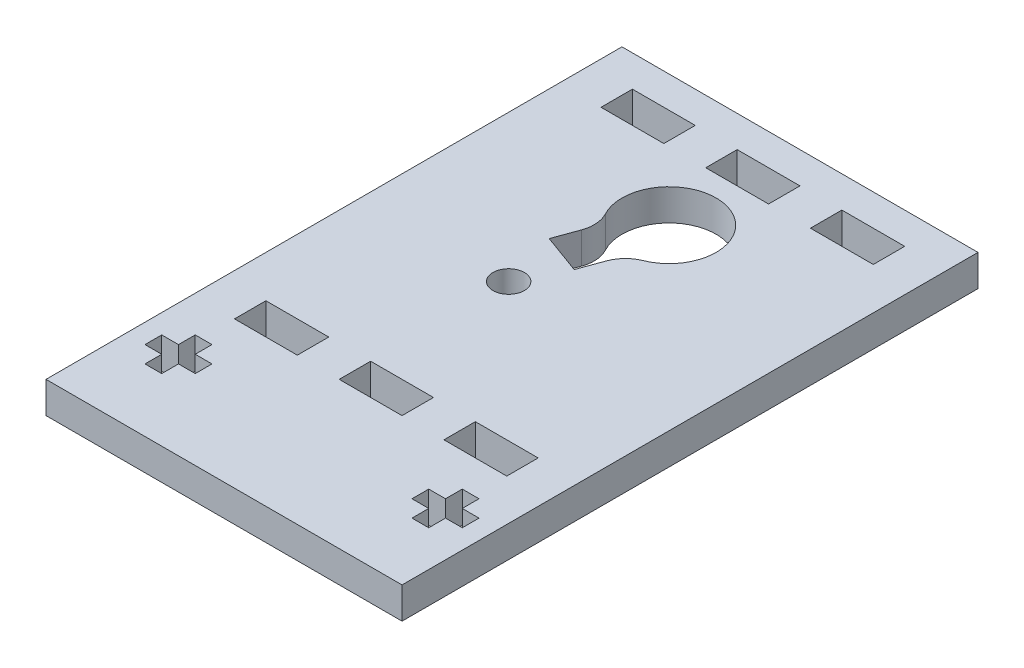
SolidWorks part; units mm, degrees
ref_plane "Front Plane" through (0, 0, 0) normal (0, 0, 1) x (1, 0, 0)
ref_plane "Top Plane" through (0, 0, 0) normal (0, 1, 0) x (1, 0, 0)
ref_plane "Right Plane" through (0, 0, 0) normal (1, 0, 0) x (0, 0, -1)
sketch "Sketch1" plane through (0, 0, 0) normal (0, 1, 0) x (1, 0, 0)
  line L1 (17, -27.5) -> (-17, -27.5)
  line L2 (17, -27.5) -> (17, 27.5)
  line L3 (17, 27.5) -> (-17, 27.5)
  line L4 (-17, -27.5) -> (-17, 27.5)
  line L5 (17, -27.5) -> (-17, 27.5) construction
  line L6 (17, 27.5) -> (-17, -27.5) construction
  point P0 (0, 0)
  dimension "D1" = 55
  dimension "D2" = 34
extrude "Boss-Extrude1" add sketch "Sketch1" along normal blind 3 contours L3 L4 L1 L2
sketch "Sketch2" plane through (0, 3, 0) normal (0, 1, 0) x (1, 0, 0)
  line L0 (-17, -27.5) -> (-17, 27.5) construction
  line L1 (17, 27.5) -> (-17, 27.5) construction
  circle A0 centre (-3, 2.6807) radius 1.5
  point P5 (0, 27.5)
  dimension "D1" = 3
  dimension "D3" = 25
  dimension "D2" = 14
extrude "Cut-Extrude1" cut sketch "Sketch2" against normal blind 3
sketch "Sketch3" [suppressed] plane through (0, 3, 0) normal (0, 1, 0) x (1, 0, 0)
  line L1 (-1.5, 12) -> (1.5, 12)
  line L2 (-1.5, 12) -> (-1.5, 8)
  line L3 (-1.5, 8) -> (1.5, 8)
  line L4 (1.5, 12) -> (1.5, 8)
  line L5 (-1.5, 12) -> (1.5, 8) construction
  line L6 (-1.5, 8) -> (1.5, 12) construction
  line L8 (17, -27.5) -> (17, 27.5) construction
  point P0 (0, 10)
  dimension "D1" = 4
  dimension "D2" = 3
  dimension "D3" = 15.5
  dimension "D4" = 8
extrude "Cut-Extrude2" [suppressed] cut sketch "Sketch3" against normal blind 3 contours L2 L3 L4 L1
sketch "Sketch4" plane through (0, 3, 0) normal (0, 1, 0) x (1, 0, 0)
  line L0 (-17, -27.5) -> (-17, 27.5) construction
  line L1 (-13.55, -16.7) -> (-11.95, -16.7)
  line L2 (-13.55, -16.7) -> (-13.55, -18.3)
  line L3 (-13.55, -21.5) -> (-11.95, -21.5)
  line L4 (-11.95, -16.7) -> (-11.95, -18.3)
  line L7 (-15.15, -18.3) -> (-13.55, -18.3)
  line L8 (-15.15, -18.3) -> (-15.15, -19.9)
  line L9 (-15.15, -19.9) -> (-13.55, -19.9)
  line L10 (-10.35, -18.3) -> (-10.35, -19.9)
  line L13 (17, -27.5) -> (-17, -27.5) construction
  line L14 (-11.95, -18.3) -> (-10.35, -18.3)
  line L17 (-11.95, -19.9) -> (-11.95, -21.5)
  line L18 (-11.95, -19.9) -> (-10.35, -19.9)
  line L19 (-13.55, -19.9) -> (-13.55, -21.5)
  point P0 (-11.1, -14.6)
  point P5 (-11.1, -14.6)
  dimension "D1" = 1.6
  dimension "D2" = 4.8
  dimension "D3" = 4.8
  dimension "D4" = 1.6
  dimension "D5" = 1.85
  dimension "D6" = 6
  dimension "D7" = 1.6
  dimension "D8" = 1.6
extrude "Cut-Extrude4" cut sketch "Sketch4" against normal blind 3
pattern_linear "LPattern1" count 2 spacing 25.5 along (1, 0, 0) of "Cut-Extrude4"
sketch "Sketch5" plane through (0, 3, 0) normal (0, 1, 0) x (1, 0, 0)
  line L0 (-17, -27.5) -> (-17, 27.5) construction
  line L1 (-13, 24.5) -> (-7, 24.5)
  line L2 (-13, 24.5) -> (-13, 21.5)
  line L3 (-13, 21.5) -> (-7, 21.5)
  line L4 (-7, 24.5) -> (-7, 21.5)
  line L5 (17, 27.5) -> (-17, 27.5) construction
  dimension "D1" = 6
  dimension "D2" = 3
  dimension "D3" = 4
  dimension "D4" = 3
extrude "Cut-Extrude5" cut sketch "Sketch5" against normal blind 3
pattern_linear "LPattern2" count 3 spacing 10 along (1, 0, 0) count 2 spacing 35 along (0, 0, 1) of "Cut-Extrude5"
sketch "Sketch6" plane through (0, 3, 0) normal (0, 1, 0) x (1, 0, 0)
  circle A0 centre (0, 15) radius 4.5
  dimension "D1" = 9
  dimension "D2" = 15
extrude "Cut-Extrude6" cut sketch "Sketch6" against normal blind 3 contours A0
fillet "Fillet2" [suppressed] radius 3
fillet "Fillet8" [suppressed] radius 3
sketch "Sketch8" plane through (0, 3, 0) normal (0, 1, 0) x (1, 0, 0)
  line L0 (0, 15) -> (-10.0352, -12.5715) construction
  line L1 (0.8533, 11.4969) -> (-2.9054, 12.865)
  line L2 (0.8533, 11.4969) -> (-0.8568, 6.7984)
  line L3 (-2.9054, 12.865) -> (-4.6155, 8.1665)
  line L4 (-0.8568, 6.7984) -> (-4.6155, 8.1665)
  dimension "D1" = 2
  dimension "D2" = 2
  dimension "D3" = 3
  dimension "D4" = 5
extrude "Cut-Extrude7" cut sketch "Sketch8" against normal blind 3
fillet "Fillet9" radius 3 1 edges at (-3.2581, 1.5, -11.896)
fillet "Fillet10" radius 3 1 edges at (0.5007, 1.5, -10.5279)
